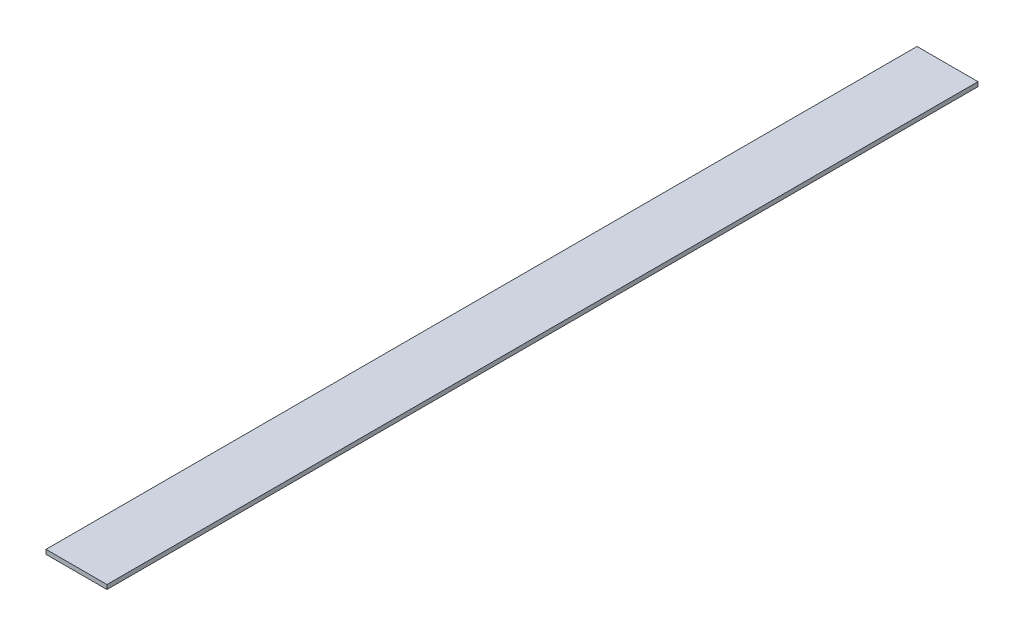
SolidWorks part; units mm, degrees
ref_plane "Front Plane" through (0, 0, 0) normal (0, 0, 1) x (1, 0, 0)
ref_plane "Top Plane" through (0, 0, 0) normal (0, 1, 0) x (1, 0, 0)
ref_plane "Right Plane" through (0, 0, 0) normal (1, 0, 0) x (0, 0, -1)
sketch "Sketch1" plane through (0, 0, 0) normal (0, 1, 0) x (1, 0, 0)
  line L1 (0, 0) -> (14, 0)
  line L2 (0, 0) -> (0, 200)
  line L3 (0, 200) -> (14, 200)
  line L4 (14, 0) -> (14, 200)
  dimension "D1" = 14
  dimension "D2" = 200
extrude "Boss-Extrude1" add sketch "Sketch1" along normal blind 1
